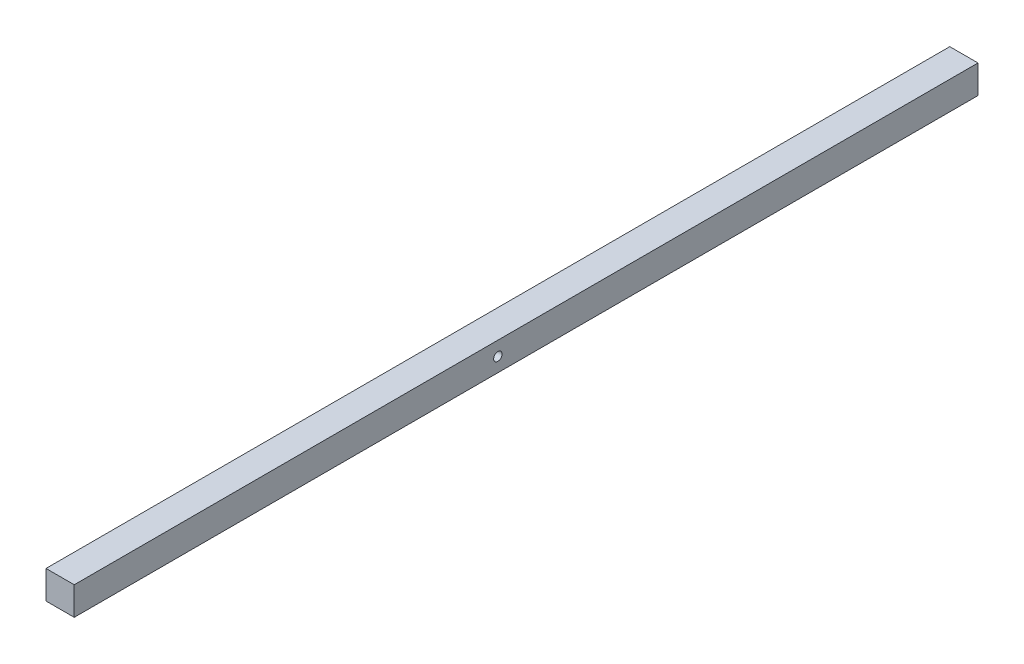
SolidWorks part; units mm, degrees
material "Sosna"
ref_plane "Płaszczyzna przednia" through (0, 0, 0) normal (0, 0, 1) x (1, 0, 0)
ref_plane "Płaszczyzna górna" through (0, 0, 0) normal (0, 1, 0) x (1, 0, 0)
ref_plane "Płaszczyzna prawa" through (0, 0, 0) normal (1, 0, 0) x (0, 0, -1)
sketch "Szkic1" plane through (0, 0, 0) normal (0, 0, 1) x (1, 0, 0)
  line L1 (0, 0) -> (20, 0)
  line L2 (0, 0) -> (0, 20)
  line L3 (0, 20) -> (20, 20)
  line L4 (20, 0) -> (20, 20)
  dimension "D1" = 20
  dimension "D2" = 20
extrude "Dodanie-wyciągnięcie1" add sketch "Szkic1" along normal blind 640
sketch "Szkic2" plane through (20, 0, 0) normal (1, 0, 0) x (0, 0, -1)
  line L0 (-640, 0) -> (0, 0) construction
  line L1 (0, 0) -> (0, 20) construction
  circle A0 centre (-340, 10) radius 3
  dimension "D1" = 6
  dimension "D2" = 10
  dimension "D3" = 340
extrude "Wytnij-wyciągnięcie1" cut sketch "Szkic2" against normal blind 8
